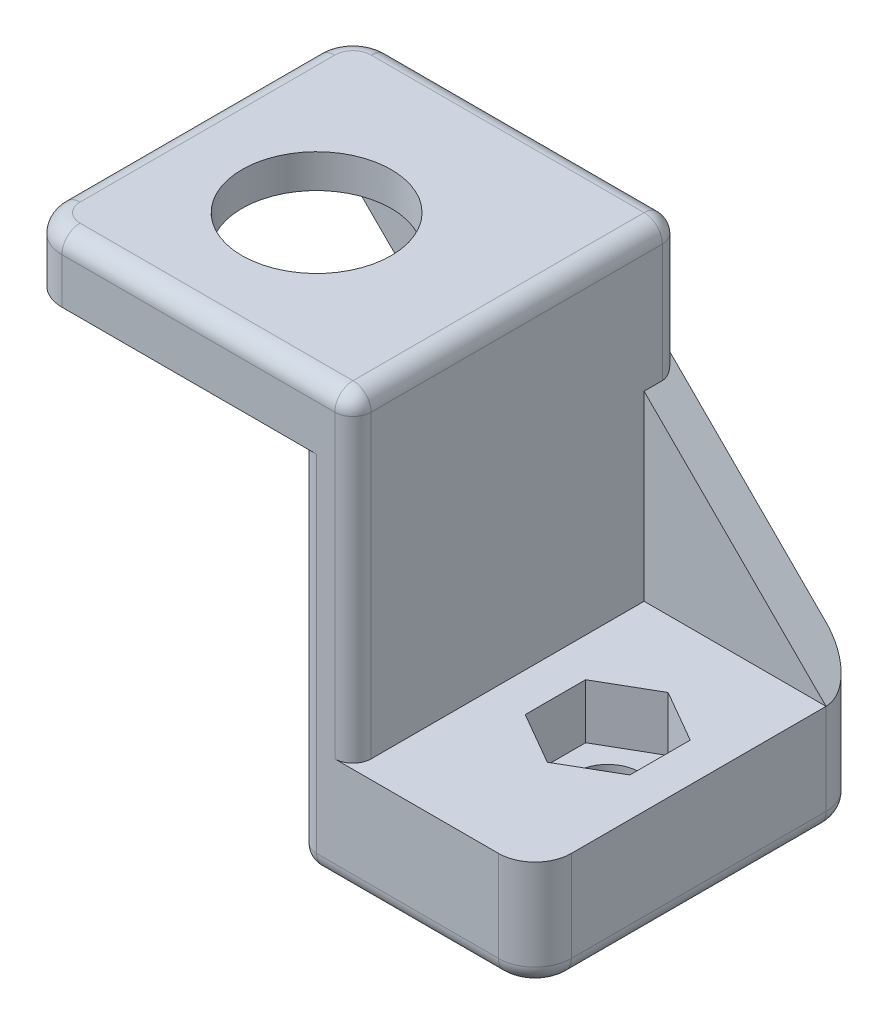
SolidWorks part; units mm, degrees
ref_plane "Front Plane" through (0, 0, 0) normal (0, 0, 1) x (1, 0, 0)
ref_plane "Top Plane" through (0, 0, 0) normal (0, 1, 0) x (1, 0, 0)
ref_plane "Right Plane" through (0, 0, 0) normal (1, 0, 0) x (0, 0, -1)
sketch "Sketch1" plane through (0, 0, 0) normal (0, 0, 1) x (1, 0, 0)
  line L0 (0, 0) -> (0, 40)
  line L1 (0, 40) -> (-30, 40)
  line L2 (-30, 40) -> (-30, 47)
  line L3 (-30, 47) -> (6, 47)
  line L4 (6, 47) -> (6, 12)
  line L5 (6, 12) -> (26, 12)
  line L6 (26, 12) -> (26, 0)
  line L7 (26, 0) -> (0, 0)
  dimension "D1" = 7
  dimension "D2" = 36
  dimension "D3" = 20
  dimension "D4" = 12
  dimension "D5" = 6
  dimension "D6" = 40
extrude "Boss-Extrude1" add sketch "Sketch1" along normal blind 36
sketch "Sketch3" plane through (0, 12, 0) normal (0, 1, 0) x (1, 0, 0)
  line L0 (16, -18) -> (26, -18) construction
  line L1 (26, -36) -> (26, 0) construction
  line L2 (16, -18) -> (6, -18) construction
  line L3 (6, -36) -> (6, 0) construction
  line L4 (16, -18) -> (16, 0) construction
  line L5 (26, 0) -> (6, 0) construction
  line L6 (16, -18) -> (16, -36) construction
  line L7 (26, -36) -> (6, -36) construction
  circle A0 centre (16, -18) radius 3.5
  dimension "D1" = 7
extrude "Cut-Extrude1" cut sketch "Sketch3" against normal blind 32
sketch "Sketch2" plane through (0, 47, 0) normal (0, 1, 0) x (1, 0, 0)
  line L0 (-30, -36) -> (-30, 0) construction
  line L3 (6, -36) -> (-30, -36) construction
  circle A0 centre (-14, -20) radius 8.2
  dimension "D1" = 16.4
  dimension "D2" = 16
  dimension "D3" = 16
extrude "Cut-Extrude2" cut sketch "Sketch2" against normal blind 32
sketch "Sketch4" plane through (0, 12, 0) normal (0, 1, 0) x (1, 0, 0)
  line L0 (26, -36) -> (26, 0) construction
  line L1 (16, -24.6395) -> (21.75, -21.3198)
  line L2 (21.75, -21.3198) -> (21.75, -14.6802)
  line L3 (21.75, -14.6802) -> (16, -11.3605)
  line L4 (16, -11.3605) -> (10.25, -14.6802)
  line L5 (10.25, -14.6802) -> (10.25, -21.3198)
  line L6 (10.25, -21.3198) -> (16, -24.6395)
  circle A0 centre (16, -18) radius 5.75 construction
  dimension "D1" = 11.5
extrude "Cut-Extrude3" cut sketch "Sketch4" against normal blind 6
sketch "Sketch5" plane through (0, 0, 0) normal (0, 0, -1) x (-1, 0, 0)
  line L0 (-26, 12) -> (-6, 32)
  line L1 (-6, 32) -> (-6, 12)
  line L2 (-6, 12) -> (-26, 12)
  line L3 (0, 10) -> (0, 40)
  line L4 (0, 40) -> (30, 40)
  line L5 (30, 40) -> (0, 10)
  line L6 (-6, 12) -> (-6, 47) construction
  line L7 (0, 40) -> (0, 0) construction
  dimension "D1" = 30
  dimension "D2" = 20
extrude "Boss-Extrude3" add sketch "Sketch5" against normal blind 4
sketch "Sketch6" plane through (0, 40, 0) normal (0, -1, 0) x (1, 0, 0)
  line L1 (-14, 4.9889) -> (-1, 12.4944)
  line L2 (-1, 12.4944) -> (-1, 27.5056)
  line L3 (-1, 27.5056) -> (-14, 35.0111)
  line L4 (-14, 35.0111) -> (-27, 27.5056)
  line L5 (-27, 27.5056) -> (-27, 12.4944)
  line L6 (-27, 12.4944) -> (-14, 4.9889)
  circle A0 centre (-14, 20) radius 13 construction
  circle A1 centre (-14, 20) radius 8.2 construction
  point P10 (0, 0)
  dimension "D1" = 26
extrude "Cut-Extrude4" cut sketch "Sketch6" against normal blind 3.3
fillet "Fillet1" radius 4 4 edges at (26, 6, 36) (26, 6, 0) (-30, 43.5, 36) (-30, 43.5, 0)
fillet "Fillet4" radius 2 15 edges at (11, 0, 36) (24.8284, 0, 34.8284) (11, 0, 0) (24.8284, 0, 1.1716) (-10, 47, 0) (-28.8284, 47, 1.1716) (-30, 47, 18) (-28.8284, 47, 34.8284) (6, 39.5, 0) (0, 20, 36) (26, 0, 18) (0, 0, 18) (-10, 47, 36) (6, 29.5, 36) (6, 47, 18)
